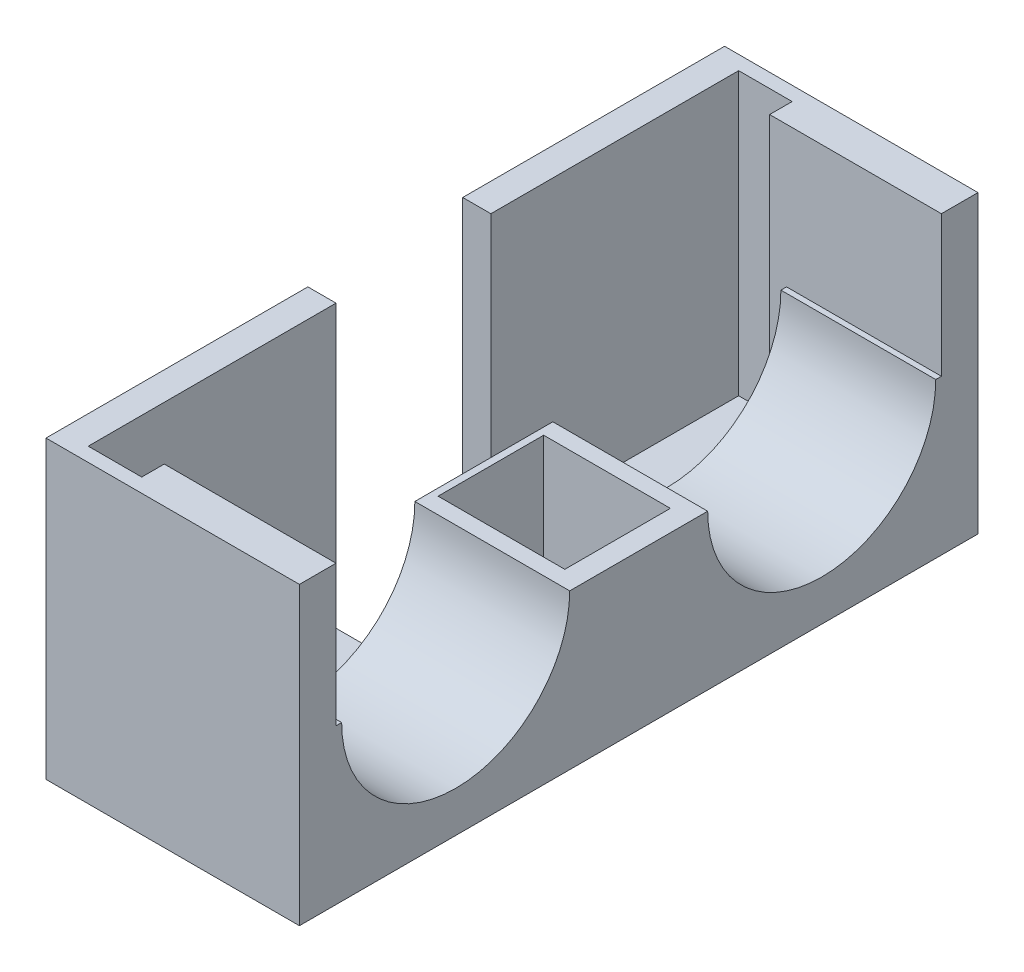
SolidWorks part; units mm, degrees
ref_plane "Front Plane" through (0, 0, 0) normal (0, 0, 1) x (1, 0, 0)
ref_plane "Top Plane" through (0, 0, 0) normal (0, 1, 0) x (1, 0, 0)
ref_plane "Right Plane" through (0, 0, 0) normal (1, 0, 0) x (0, 0, -1)
sketch "Sketch1" plane through (0, 0, 0) normal (0, 1, 0) x (1, 0, 0)
  line L1 (-12.5, -24.1) -> (12.5, -24.1)
  line L2 (-12.5, -24.1) -> (-12.5, 24.1)
  line L3 (-12.5, 24.1) -> (12.5, 24.1)
  line L4 (12.5, -24.1) -> (12.5, 24.1)
  line L5 (-12.5, -24.1) -> (12.5, 24.1) construction
  line L6 (-12.5, 24.1) -> (12.5, -24.1) construction
  point P0 (0, 0)
  dimension "D1" = 48.2
  dimension "D2" = 25
extrude "Boss-Extrude1" add sketch "Sketch1" along normal blind 1
sketch "Sketch2" plane through (0, 1, 0) normal (0, 1, 0) x (1, 0, 0)
  line L0 (-55, 0) -> (55, 0) construction
  line L1 (-9.5, -21.5) -> (1.5, -21.5)
  line L2 (-9.5, -21.5) -> (-9.5, 21.5)
  line L3 (-9.5, 21.5) -> (1.5, 21.5)
  line L4 (1.5, -21.5) -> (1.5, 21.5)
  line L5 (-9.5, -21.5) -> (1.5, 21.5) construction
  line L6 (-9.5, 21.5) -> (1.5, -21.5) construction
  line L7 (-12.5, 24.1) -> (-12.5, -24.1) construction
  point P0 (-4, 0)
  point P9 (0, 0)
  dimension "D1" = 3
  dimension "D2" = 43
  dimension "D3" = 11
extrude "Boss-Extrude2" add sketch "Sketch2" along normal blind 10
sketch "Sketch3" plane through (1.5, 0, 0) normal (1, 0, 0) x (0, 0, -1)
  line L0 (0, 55) -> (0, -55) construction
  line L1 (-21.5, 11) -> (21.5, 11) construction
  circle A0 centre (-13, 11) radius 8.1
  circle A1 centre (13, 11) radius 8.1
  point P8 (0, 0)
  dimension "D1" = 16.2
  dimension "D2" = 0
  dimension "D3" = 13
  dimension "D4" = 13
  dimension "D5" = 0
extrude "Cut-Extrude1" cut sketch "Sketch3" against normal up to vertex (11 mm away)
sketch "Sketch4" plane through (0, 1, 0) normal (0, 1, 0) x (1, 0, 0)
  line L0 (-9.5, -21.5) -> (-10.7, -21.5)
  line L1 (-10.7, -21.5) -> (-10.7, -23.1)
  line L2 (-10.7, -23.1) -> (-12.5, -23.1)
  line L3 (-12.5, 24.1) -> (-12.5, -24.1) construction
  line L4 (-12.5, -23.1) -> (-12.5, -24.1)
  line L10 (1.5, -21.5) -> (-9.5, -21.5)
  line L12 (1.5, -21.5) -> (1.5, -24.1)
  line L13 (1.5, -24.1) -> (-12.5, -24.1)
  dimension "D1" = 1.6
  dimension "D2" = 1.8
  dimension "D4" = 1
extrude "Boss-Extrude3" add sketch "Sketch4" along normal blind 20
mirror "Mirror2" about plane through (0, 0, 0) normal (0, 0, 1) of "Boss-Extrude3"
sketch "Sketch5" plane through (-12.5, 0, 0) normal (-1, 0, 0) x (0, 0, 1)
  line L0 (-24.1, 21) -> (-23.1, 21)
  line L1 (-23.1, 21) -> (-23.1, 1)
  line L2 (-23.1, 1) -> (23.1, 1)
  line L3 (23.1, 1) -> (23.1, 21)
  line L4 (23.1, 21) -> (24.1, 21)
  line L5 (24.1, 21) -> (24.1, 0)
  line L6 (-24.1, 0) -> (24.1, 0) construction
  line L7 (24.1, 0) -> (-24.1, 0)
  line L8 (-24.1, 0) -> (-24.1, 21)
extrude "Boss-Extrude4" add sketch "Sketch5" along normal blind 2
sketch "Sketch7" plane through (-14.5, 0, 0) normal (-1, 0, 0) x (0, 0, 1)
  line L1 (-24.1, 21) -> (24.1, 21)
  line L2 (-24.1, 21) -> (-24.1, 0)
  line L3 (-24.1, 0) -> (24.1, 0)
  line L4 (24.1, 21) -> (24.1, 0)
extrude "Boss-Extrude5" add sketch "Sketch7" along normal blind 2
sketch "Sketch8" plane through (0, 1, 0) normal (0, 1, 0) x (1, 0, 0)
  line L0 (-55, 0) -> (55, 0) construction
  line L1 (-16.5, -5.5) -> (-12.5, -5.5)
  line L2 (-16.5, -5.5) -> (-16.5, 5.5)
  line L3 (-16.5, 5.5) -> (-12.5, 5.5)
  line L4 (-12.5, -5.5) -> (-12.5, 5.5)
  line L5 (-16.5, -5.5) -> (-12.5, 5.5) construction
  line L6 (-16.5, 5.5) -> (-12.5, -5.5) construction
  line L7 (-16.5, -24.1) -> (-16.5, 24.1) construction
  point P0 (-14.5, 0)
  dimension "D1" = 0
  dimension "D2" = 4
  dimension "D3" = 11
extrude "Cut-Extrude2" cut sketch "Sketch8" against normal up to vertex (1 mm away) and the other way up to vertex (20 mm away)
sketch "Sketch9" plane through (0, 11, 0) normal (0, 1, 0) x (1, 0, 0)
  line L0 (-55, 0) -> (55, 0) construction
  line L1 (-9, -3.75) -> (0, -3.75)
  line L2 (-9, -3.75) -> (-9, 3.75)
  line L3 (-9, 3.75) -> (0, 3.75)
  line L4 (0, -3.75) -> (0, 3.75)
  line L5 (-9, -3.75) -> (0, 3.75) construction
  line L6 (-9, 3.75) -> (0, -3.75) construction
  line L7 (0, -55) -> (0, 55) construction
  point P0 (-4.5, 0)
  dimension "D1" = 9
  dimension "D2" = 7.5
extrude "Cut-Extrude3" cut sketch "Sketch9" against normal up to vertex (10 mm away)
sketch "Sketch10" plane through (0, 1, 0) normal (0, 1, 0) x (1, 0, 0)
  line L0 (-9, 3.75) -> (-9, -3.75) construction
  line L1 (-9, -3.75) -> (0, -3.75) construction
  line L2 (-9, 3.75) -> (-9, -3.75) construction
  line L3 (-55, 0) -> (55, 0) construction
  circle A0 centre (-4.5, 0) radius 0.75
  circle A1 centre (-3.75, 2.5) radius 0.5
  circle A2 centre (-3.75, -2.5) radius 0.5
  dimension "D2" = 1.5
  dimension "D4" = 1
  dimension "D1" = 4.5
  dimension "D3" = 3.75
  dimension "D5" = 2.5
  dimension "D6" = 5.25
  dimension "D7" = 2.5
  dimension "D8" = 5.25
extrude "Cut-Extrude4" cut sketch "Sketch10" against normal up to vertex (1 mm away)
sketch "Sketch11" plane through (0, 1, 0) normal (0, 1, 0) x (1, 0, 0)
  line L0 (12.5, -24.1) -> (12.5, 24.1) construction
  line L1 (1.5, 24.1) -> (12.5, 24.1)
  line L2 (1.5, 24.1) -> (1.5, -24.1)
  line L3 (1.5, -24.1) -> (12.5, -24.1)
  line L4 (12.5, 24.1) -> (12.5, -24.1)
  line L5 (1.5, -24.1) -> (12.5, -24.1) construction
extrude "Cut-Extrude5" cut sketch "Sketch11" against normal up to vertex (1 mm away)
